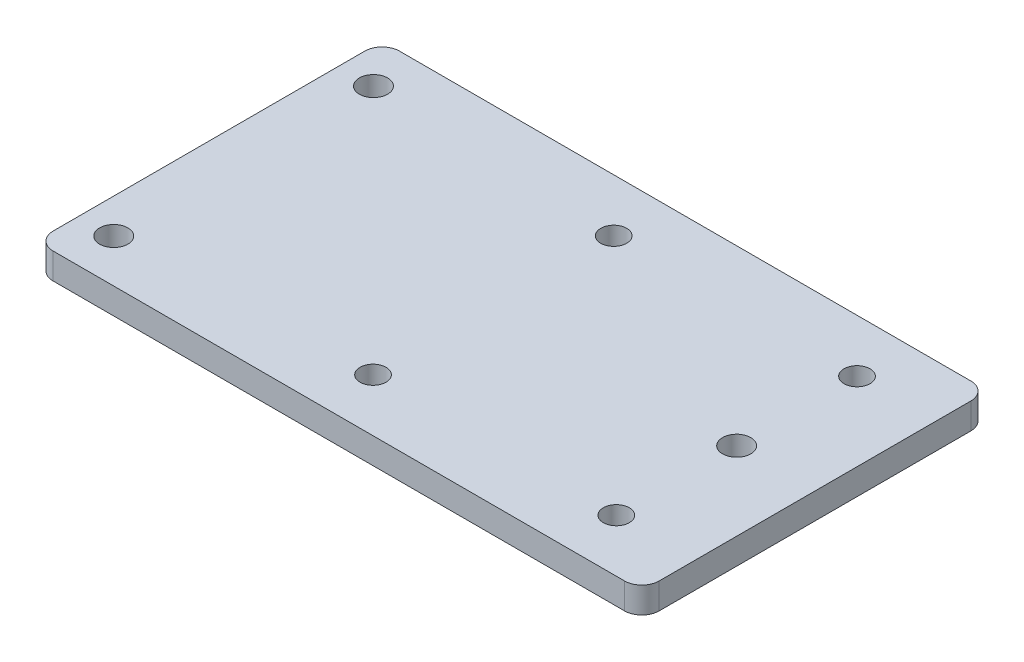
SolidWorks part; units mm, degrees
material "Acrylic (Medium-high impact)"
ref_plane "Front Plane" through (0, 0, 0) normal (0, 0, 1) x (1, 0, 0)
ref_plane "Top Plane" through (0, 0, 0) normal (0, 1, 0) x (1, 0, 0)
ref_plane "Right Plane" through (0, 0, 0) normal (1, 0, 0) x (0, 0, -1)
sketch "Sketch1" plane through (0, 0, 0) normal (0, 1, 0) x (1, 0, 0)
  line L1 (-35, 20) -> (35, 20)
  line L2 (-35, 20) -> (-35, -20)
  line L3 (-35, -20) -> (35, -20)
  line L4 (35, 20) -> (35, -20)
  line L5 (-35, 20) -> (35, -20) construction
  line L6 (-35, -20) -> (35, 20) construction
  point P0 (0, 0)
  dimension "D1" = 70
  dimension "D2" = 40
extrude "Boss-Extrude1" add sketch "Sketch1" along normal blind 3
hole_wizard "Ø3.0mm Dowel Hole1" positions "Sketch2" profile "Sketch3" hole size "Ø3.0" standard "ANSI Metric" end condition through all
sketch "Sketch2" plane through (0, 3, 0) normal (0, 1, 0) x (1, 0, 0)
  line L2 (35, -20) -> (35, 20) construction
  line L3 (-35, -20) -> (35, -20) construction
  point P0 (-2.15, 13.9)
  point P2 (25.95, 13.9)
  point P4 (-2.15, -13.9)
  point P6 (25.95, -13.9)
  dimension "D3" = 27.8
  dimension "D1" = 37.15
  dimension "D2" = 9.05
  dimension "D4" = 6.1
sketch "Sketch3" plane through (-2.15, 3, -13.9) normal (1, 0, 0) x (0, 0, 1)
  line L0 (0, 0) -> (0, 3)
  line L1 (0, 3) -> (1.5, 3)
  line L2 (1.5, 3) -> (1.5, 0)
  line L5 (1.5, 0) -> (0, 0)
  line L11 (0, -6.35) -> (0, 107.95) construction
  dimension "Thru Hole Dia." = 3
  dimension "Thru Hole Depth" = 3
hole_wizard "#4 Clearance Hole1" positions "Sketch4" profile "Sketch5" hole size "#4" standard "ANSI Inch" end condition through all
sketch "Sketch4" plane through (0, 3, 0) normal (0, 1, 0) x (1, 0, 0)
  line L0 (-35, 20) -> (-35, -20) construction
  line L1 (-35, -20) -> (35, -20) construction
  line L2 (35, 20) -> (-35, 20) construction
  line L3 (35, -20) -> (35, 20) construction
  point P0 (-31, 15)
  point P2 (-31, -15)
  point P11 (25.95, 0)
  dimension "D1" = 4
  dimension "D2" = 4
  dimension "D3" = 5
  dimension "D4" = 5
  dimension "D5" = 9.05
sketch "Sketch5" plane through (-31, 3, -15) normal (1, 0, 0) x (0, 0, 1)
  line L0 (0, 0) -> (0, 3)
  line L1 (0, 3) -> (1.6319, 3)
  line L2 (1.6319, 3) -> (1.6319, 0)
  line L5 (1.6319, 0) -> (0, 0)
  line L11 (0, -6.35) -> (0, 107.95) construction
  dimension "Thru Hole Dia." = 3.2639
  dimension "Thru Hole Depth" = 3
fillet "Fillet1" radius 2 4 edges at (-35, 1.5, -20) (-35, 1.5, 20) (35, 1.5, -20) (35, 1.5, 20)
equation "\"D4@Sketch2\"=(40-\"D3@Sketch2\")/2"
equation "\"D4@Sketch4\"=\"D3@Sketch4\""
equation "\"D2@Sketch4\"=\"D1@Sketch4\""
